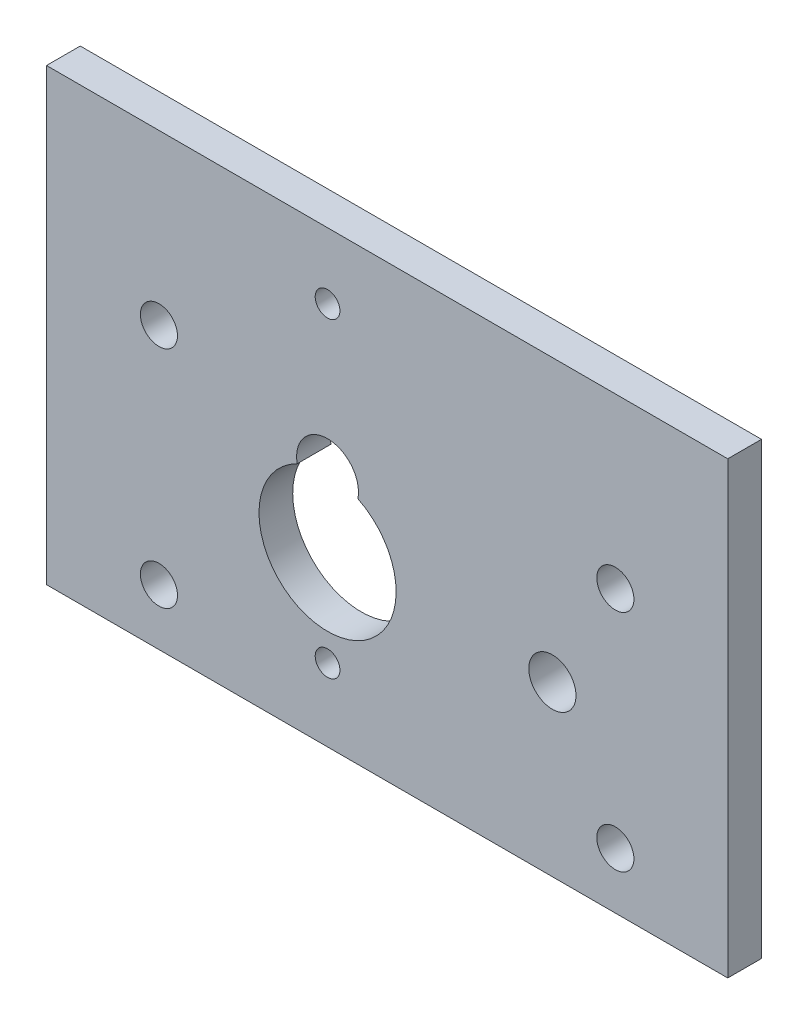
SolidWorks part; units mm, degrees
ref_plane "前视基准面" through (0, 0, 0) normal (0, 0, 1) x (1, 0, 0)
ref_plane "上视基准面" through (0, 0, 0) normal (0, 1, 0) x (1, 0, 0)
ref_plane "右视基准面" through (0, 0, 0) normal (1, 0, 0) x (0, 0, -1)
sketch "草图1" plane through (0, 0, 0) normal (0, 0, 1) x (1, 0, 0)
  line L1 (0, 0) -> (60.6, 0)
  line L2 (0, 0) -> (0, 40)
  line L3 (0, 40) -> (60.6, 40)
  line L4 (60.6, 0) -> (60.6, 40)
  dimension "D1" = 60.6
  dimension "D2" = 40
extrude "凸台-拉伸1" add sketch "草图1" along normal blind 3
sketch "草图2" plane through (0, 0, 0) normal (0, 0, -1) x (-1, 0, 0)
  line L0 (-25, 0) -> (-25, 40) construction
  line L1 (0, 0) -> (-60.6, 0) construction
  line L2 (-60.6, 40) -> (0, 40) construction
  line L3 (0, 40) -> (0, 0) construction
  line L4 (-45, 40) -> (-45, 0) construction
  line L5 (-25, 15) -> (-45, 15) construction
  circle A0 centre (-25, 6.46) radius 1.1
  circle A1 centre (-25, 15) radius 6.1
  circle A2 centre (-25, 21) radius 2.75
  circle A3 centre (-25, 34.14) radius 1.1
  circle A4 centre (-45, 15) radius 2.1
  dimension "D2" = 2.2
  dimension "D3" = 2.2
  dimension "D4" = 12.2
  dimension "D5" = 5.5
  dimension "D8" = 19.14
  dimension "D11" = 4.2
  dimension "D1" = 25
  dimension "D6" = 6
  dimension "D7" = 8.54
  dimension "D9" = 15
  dimension "D10" = 20
extrude "切除-拉伸1" cut sketch "草图2" against normal through all contours A2 A1 | A1 A2 | A1 A2 | A0 | A3 | A4
sketch "草图3" plane through (0, 0, 3) normal (0, 0, 1) x (1, 0, 0)
  line L0 (50.6, 0) -> (50.6, 40) construction
  line L1 (0, 0) -> (60.6, 0) construction
  line L2 (60.6, 40) -> (0, 40) construction
  line L3 (10, 0) -> (10, 40) construction
  line L4 (0, 40) -> (0, 0) construction
  line L5 (60.6, 0) -> (60.6, 40) construction
  circle A0 centre (50.6, 5) radius 1.65
  circle A1 centre (50.6, 25) radius 1.65
  circle A2 centre (10, 25) radius 1.65
  circle A3 centre (10, 5) radius 1.65
  dimension "D7" = 3.3
  dimension "D1" = 10
  dimension "D2" = 10
  dimension "D3" = 15
  dimension "D4" = 5
  dimension "D5" = 5
  dimension "D6" = 15
extrude "切除-拉伸2" cut sketch "草图3" against normal blind 13
